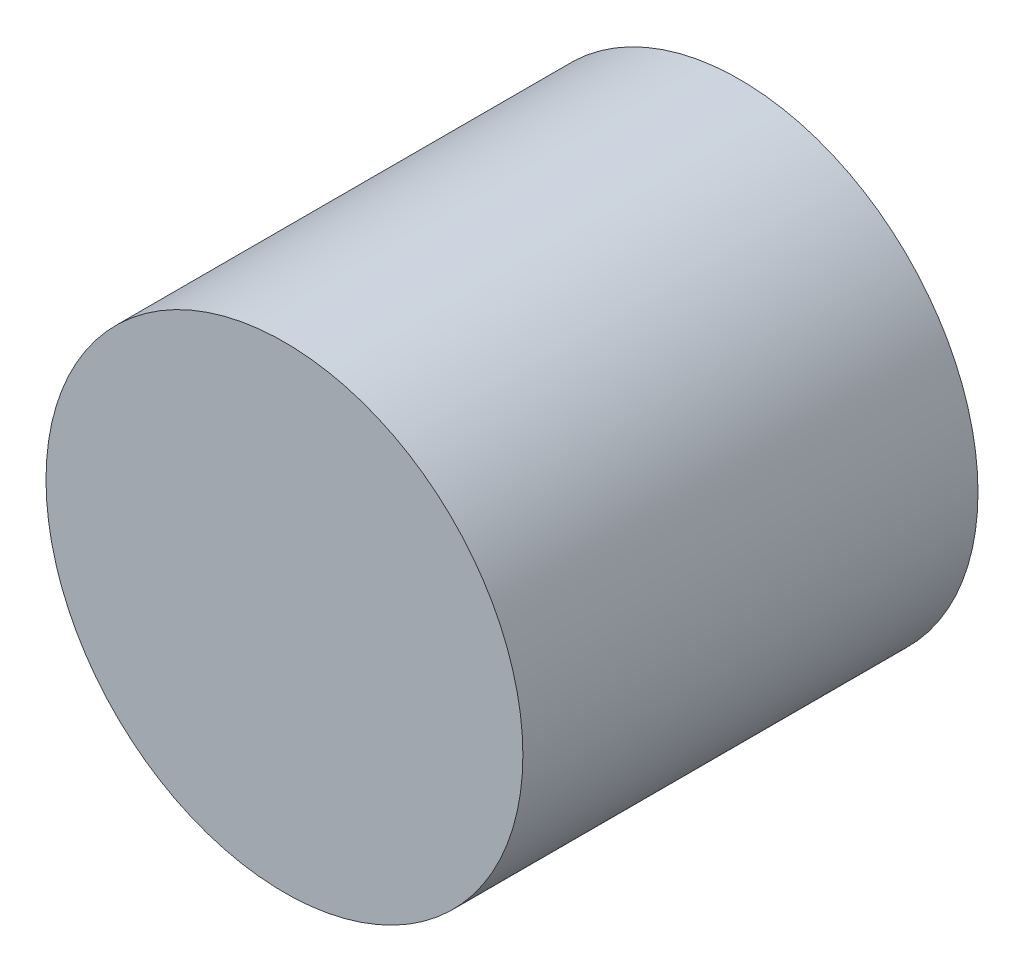
SolidWorks part; units mm, degrees
ref_plane "Front Plane" through (0, 0, 0) normal (0, 0, 1) x (1, 0, 0)
ref_plane "Top Plane" through (0, 0, 0) normal (0, 1, 0) x (1, 0, 0)
ref_plane "Right Plane" through (0, 0, 0) normal (1, 0, 0) x (0, 0, -1)
sketch "CurveSketch" plane through (0, 0, 0) normal (0, 0, 1) x (1, 0, 0)
  circle A0 centre (-3.719, 6.137) radius 5.5565
  dimension "D1" = 11.113
extrude "CurveBoss" add sketch "CurveSketch" along normal blind 10.6061
